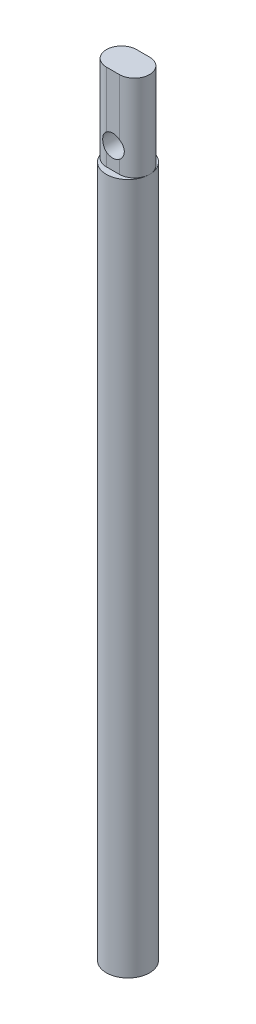
SolidWorks part; units mm, degrees
ref_plane "Front Plane" through (0, 0, 0) normal (0, 0, 1) x (1, 0, 0)
ref_plane "Top Plane" through (0, 0, 0) normal (0, 1, 0) x (1, 0, 0)
ref_plane "Right Plane" through (0, 0, 0) normal (1, 0, 0) x (0, 0, -1)
sketch "Sketch1" plane through (0, 0, 0) normal (0, 1, 0) x (1, 0, 0)
  circle A0 centre (0, 0) radius 5
  dimension "D1" = 10
extrude "Boss-Extrude1" add sketch "Sketch1" along normal blind 160
sketch "Sketch2" plane through (0, 160, 0) normal (0, 1, 0) x (1, 0, 0)
  line L0 (1.5, 0) -> (-1.5, 0) construction
  line L1 (1.5, -3.5) -> (-1.5, -3.5)
  line L2 (1.5, 3.5) -> (-1.5, 3.5)
  arc A0 (1.5, -3.5) -> (1.5, 3.5) centre (1.5, 0) ccw
  arc A1 (-1.5, 3.5) -> (-1.5, -3.5) centre (-1.5, 0) ccw
  point P2 (0, 0)
  point P8 (-5, 0)
  point P9 (5, 0)
  dimension "D1" = 10
  dimension "D2" = 7
extrude "Boss-Extrude2" add sketch "Sketch2" along normal blind 20
sketch "Sketch3" plane through (0, 0, 3.5) normal (0, 0, 1) x (1, 0, 0)
  line L0 (-1.5, 160) -> (1.5, 160) construction
  line L1 (5, 160) -> (5, 180) construction
  circle A0 centre (0, 165) radius 2.5
  dimension "D2" = 5
  dimension "D1" = 5
  dimension "D3" = 5
extrude "Cut-Extrude1" cut sketch "Sketch3" against normal blind 10
